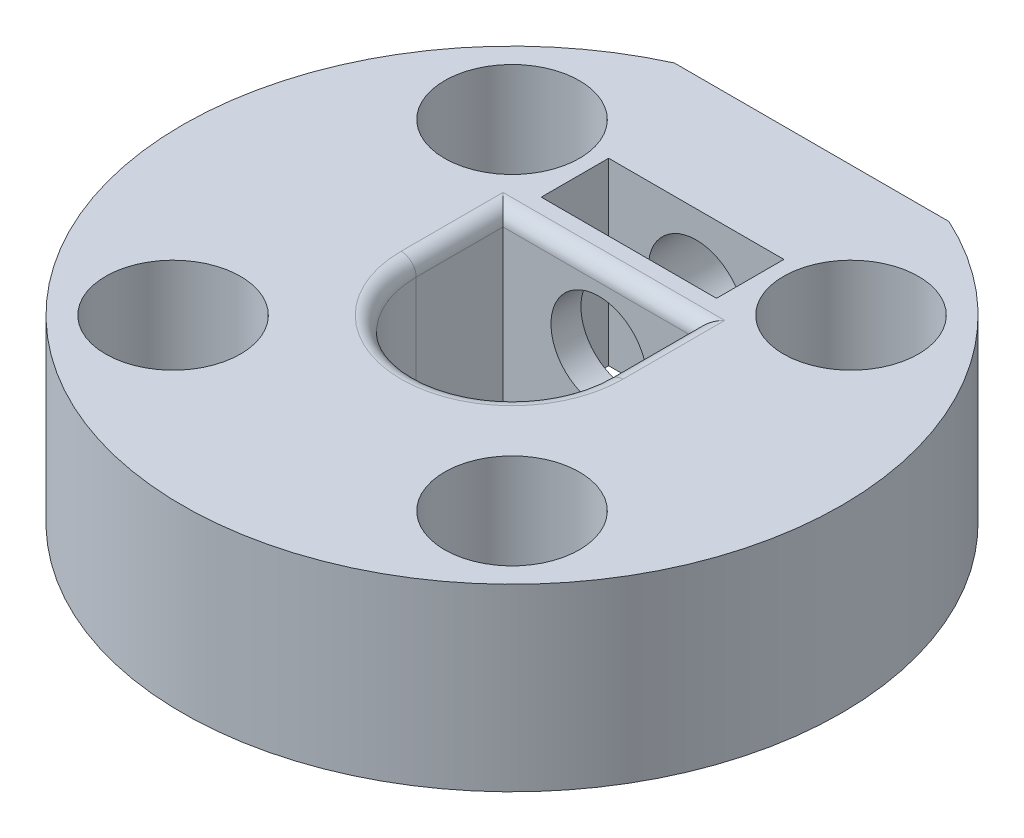
SolidWorks part; units mm, degrees
ref_plane "Plan de face" through (0, 0, 0) normal (0, 0, 1) x (1, 0, 0)
ref_plane "Plan de dessus" through (0, 0, 0) normal (0, 1, 0) x (1, 0, 0)
ref_plane "Plan de droite" through (0, 0, 0) normal (1, 0, 0) x (0, 0, -1)
sketch "Esquisse1" plane through (0, 0, 0) normal (0, 1, 0) x (1, 0, 0)
  line L1 (-3.2, 0) -> (-3.2, 2.9)
  line L2 (3.2, 0) -> (3.2, 2.9)
  line L3 (3.2, 2.9) -> (-3.2, 2.9)
  line L4 (4.5826, 10) -> (-4.5826, 10)
  arc A0 (-4.5826, 10) -> (4.5826, 10) centre (0, 0) ccw
  arc A1 (-3.2, 0) -> (3.2, 0) centre (0, 0) ccw
  point P10 (0, 2.9)
  dimension "D1" = 22
  dimension "D2" = 6.4
  dimension "D3" = 2.9
  dimension "D4" = 10
extrude "Boss.-Extru.1" add sketch "Esquisse1" along normal blind 6
hole_wizard "Chambrage pour vis à tête cylindrique à 6 pans creux (ou vis CHC) M21" positions "Esquisse2" profile "Esquisse3" counterbore size "M2" standard "Ansi Metric" end condition through all
sketch "Esquisse2" plane through (0, 6, 0) normal (0, 1, 0) x (1, 0, 0)
  line L0 (0, 0) -> (6.1221, 0) construction
  line L2 (0, 0) -> (9.471, 9.471) construction
  point P0 (5.6569, 5.6569)
  point P28 (5.6569, -5.6569)
  point P29 (-5.6569, -5.6569)
  point P30 (-5.6569, 5.6569)
  point P31 (0, 0)
  dimension "D1" = 8
  dimension "D3" = 45
  dimension "D2" = 4
sketch "Esquisse3" plane through (5.6569, 6, -5.6569) normal (1, 0, 0) x (0, 0, 1)
  line L0 (0, 0) -> (0, 6)
  line L1 (0, 6) -> (1.25, 6)
  line L3 (1.25, 6) -> (1.25, 4.5)
  line L4 (1.25, 4.5) -> (2.25, 4.5)
  line L5 (2.25, 4.5) -> (2.25, 0)
  line L7 (2.25, 0) -> (0, 0)
  line L11 (0, -6.35) -> (0, 107.95) construction
  dimension "Diamètre du perçage jusqu'au prochain" = 2.5
  dimension "Profondeur du perçage jusqu'au prochain" = 6
  dimension "Diamètre du chambrage" = 4.5
  dimension "Profondeur du chambrage" = 4.5
fillet "Congé1" radius 0.5 4 edges at (0, 6, 3.2) (-3.2, 6, -1.45) (3.2, 6, -1.45) (0, 6, -2.9)
sketch "Esquisse6" plane through (0, 0, 0) normal (0, 0, 1) x (1, 0, 0)
  line L0 (0, 0) -> (0, 6) construction
  line L1 (11, 6) -> (-11, 6) construction
  line L2 (11, 6) -> (-11, 6) construction
  circle A0 centre (0, 3.5) radius 1.6
  dimension "D1" = 3.2
  dimension "D2" = 2.5
extrude "Enlèv. mat.-Extru.1" cut sketch "Esquisse6" against normal through all
sketch "Esquisse7" plane through (0, 6, 0) normal (0, 1, 0) x (1, 0, 0)
  line L1 (-2.925, 3.9) -> (2.925, 3.9)
  line L2 (-2.925, 3.9) -> (-2.925, 6.15)
  line L3 (-2.925, 6.15) -> (2.925, 6.15)
  line L4 (2.925, 3.9) -> (2.925, 6.15)
  line L5 (-2.925, 3.9) -> (2.925, 6.15) construction
  line L6 (-2.925, 6.15) -> (2.925, 3.9) construction
  line L7 (3.2, 2.9) -> (-3.2, 2.9) construction
  point P0 (0, 5.025)
  dimension "D3" = 1
  dimension "D1" = 2.25
  dimension "D2" = 5.85
extrude "Enlèv. mat.-Extru.2" cut sketch "Esquisse7" against normal through all
